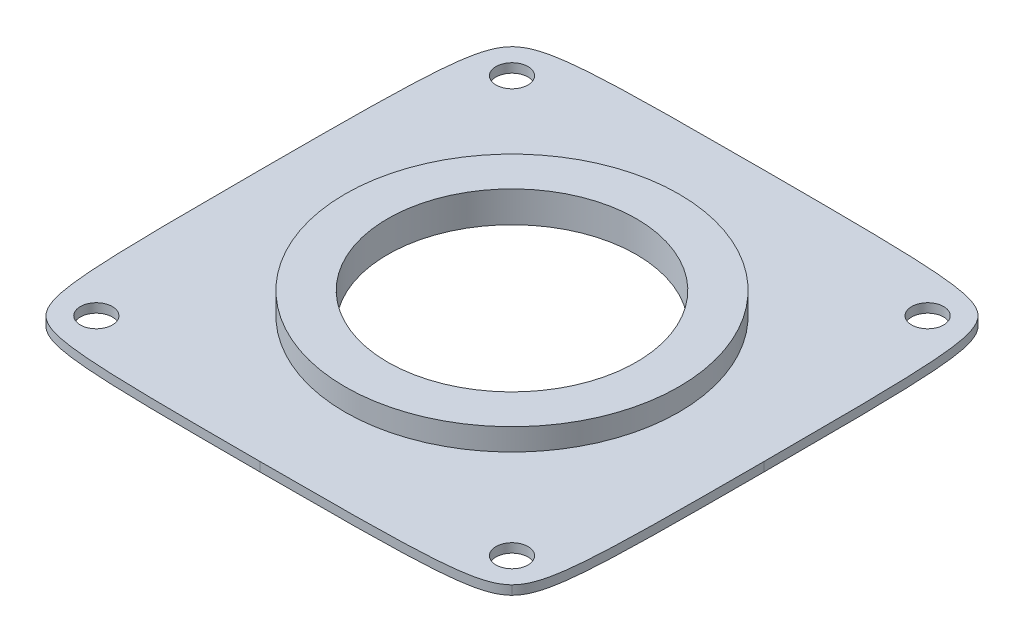
SolidWorks part; units mm, degrees
ref_plane "Front Plane" through (0, 0, 0) normal (0, 0, 1) x (1, 0, 0)
ref_plane "Top Plane" through (0, 0, 0) normal (0, 1, 0) x (1, 0, 0)
ref_plane "Right Plane" through (0, 0, 0) normal (1, 0, 0) x (0, 0, -1)
sketch "Sketch1" plane through (0, 0, 0) normal (0, 1, 0) x (1, 0, 0)
  line L0 (-38.8094, 26.7808) -> (-26.7808, 38.8094) construction
  line L5 (-32.7951, -32.7951) -> (32.7951, 32.7951) construction
  line L6 (-32.7951, 32.7951) -> (32.7951, -32.7951) construction
  line L8 (-35.5, 0) -> (35.5, 0) construction
  line L9 (0, 35.5) -> (0, -35.5) construction
  circle A0 centre (29.253, 29.253) radius 2.25
  circle A1 centre (29.253, -29.253) radius 2.25
  circle A2 centre (-29.253, -29.253) radius 2.25
  circle A3 centre (-29.253, 29.253) radius 2.25
  circle A4 centre (0, 0) radius 17.5
  spline S0 degree 3 poles (0, 35.5) (-24.0687, 35.5) (-30.2979, 35.2922) (-32.7951, 32.7951) knots 0 0 0 0 1 1 1 1
  spline S1 degree 3 poles (-35.5, 0) (-35.5, 24.0687) (-35.2922, 30.2979) (-32.7951, 32.7951) knots 0 0 0 0 1 1 1 1
  spline S2 degree 3 poles (35.5, 0) (35.5, 24.0687) (35.2922, 30.2979) (32.7951, 32.7951) knots 0 0 0 0 1 1 1 1
  spline S3 degree 3 poles (0, 35.5) (24.0687, 35.5) (30.2979, 35.2922) (32.7951, 32.7951) knots 0 0 0 0 1 1 1 1
  spline S4 degree 3 poles (35.5, 0) (35.5, -24.0687) (35.2922, -30.2979) (32.7951, -32.7951) knots 0 0 0 0 1 1 1 1
  spline S5 degree 3 poles (0, -35.5) (24.0687, -35.5) (30.2979, -35.2922) (32.7951, -32.7951) knots 0 0 0 0 1 1 1 1
  spline S6 degree 3 poles (0, -35.5) (-24.0687, -35.5) (-30.2979, -35.2922) (-32.7951, -32.7951) knots 0 0 0 0 1 1 1 1
  spline S7 degree 3 poles (-35.5, 0) (-35.5, -24.0687) (-35.2922, -30.2979) (-32.7951, -32.7951) knots 0 0 0 0 1 1 1 1
  point P0 (0, 0)
  point P11 (0, 0)
  point P14 (0, 0)
  point P17 (0, 0)
  point P20 (0, 0)
  dimension "D4" = 4.5
  dimension "D6" = 35
  dimension "D7" = 90
  dimension "D3" = 41.37
  dimension "D5" = 4
extrude "Boss-Extrude1" add sketch "Sketch1" along normal blind 1.28
sketch "Sketch2" plane through (0, 1.28, 0) normal (0, 1, 0) x (1, 0, 0)
  circle A0 centre (0, 0) radius 23.5
  circle A1 centre (0, 0) radius 17.5 construction
  circle A2 centre (0, 0) radius 17.5
  circle A3 centre (0, 0) radius 17.5
  circle M4 centre (0, 0) radius 17.5
  dimension "D1" = 6
extrude "Boss-Extrude2" add sketch "Sketch2" along normal blind 3.09 contours A0 M4
sketch "Sketch3" plane through (0, 0, 0) normal (0, -1, 0) x (1, 0, 0)
  line L0 (-29.253, 29.253) -> (29.253, -29.253)
  line L1 (29.253, 29.253) -> (-29.253, -29.253)
  line L2 (-27.7838, 0) -> (25.335, 0)
  line L3 (0, 29.253) -> (0, -25.8059)
